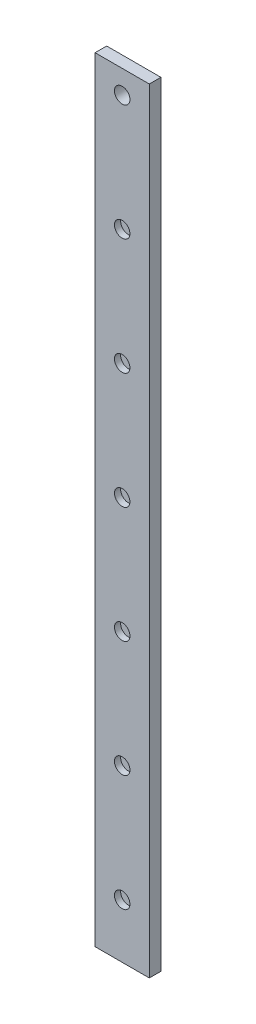
SolidWorks part; units mm, degrees
ref_plane "Front Plane" through (0, 0, 0) normal (0, 0, 1) x (1, 0, 0)
ref_plane "Top Plane" through (0, 0, 0) normal (0, 1, 0) x (1, 0, 0)
ref_plane "Right Plane" through (0, 0, 0) normal (1, 0, 0) x (0, 0, -1)
sketch "Sketch1" plane through (0, 0, 0) normal (0, 1, 0) x (1, 0, 0)
  line L1 (0, 0) -> (-70, 0)
  line L2 (0, 0) -> (0, -15)
  line L3 (0, -15) -> (-70, -15)
  line L4 (-70, 0) -> (-70, -15)
  dimension "D1" = 70
  dimension "D2" = 15
extrude "Boss-Extrude1" add sketch "Sketch1" along normal blind 1000 contours L1 L4 L3 L2
sketch "Sketch2" plane through (0, 0, 15) normal (0, 0, 1) x (1, 0, 0)
  line L0 (0, 1000) -> (0, 0) construction
  line L1 (0, 1000) -> (-70, 1000) construction
  circle A0 centre (-35, 970) radius 10
  dimension "D1" = 20
  dimension "D2" = 35
  dimension "D3" = 30
extrude "Cut-Extrude1" cut sketch "Sketch2" against normal blind 15 contours A0
sketch "Sketch3" plane through (0, 0, 15) normal (0, 0, 1) x (1, 0, 0)
  line L0 (0, 1000) -> (0, 0) construction
  circle A0 centre (-35, 820) radius 10
  circle A1 centre (-35, 970) radius 10 construction
  circle A7 centre (-35, 670) radius 10
  circle A8 centre (-35, 520) radius 10
  circle A9 centre (-35, 370) radius 10
  circle A10 centre (-35, 220) radius 10
  circle A11 centre (-35, 70) radius 10
  point P18 (0, 0)
  point P19 (0, 0)
  dimension "D1" = 20
  dimension "D2" = 35
  dimension "D3" = 150
  dimension "D5" = 150
  dimension "D4" = 6
extrude "Cut-Extrude2" cut sketch "Sketch3" against normal blind 8
